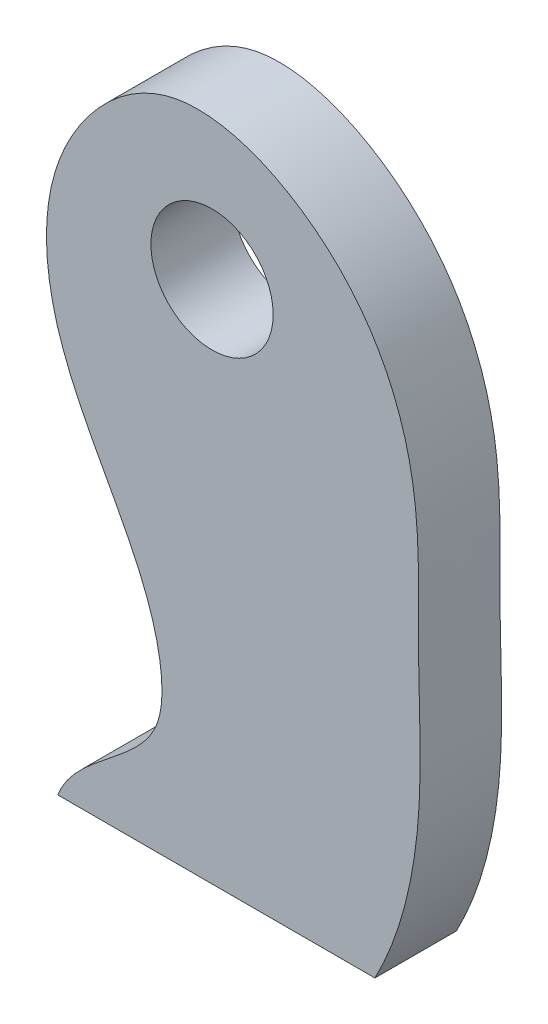
SolidWorks part; units mm, degrees
ref_plane "Front Plane" through (0, 0, 0) normal (0, 0, 1) x (1, 0, 0)
ref_plane "Top Plane" through (0, 0, 0) normal (0, 1, 0) x (1, 0, 0)
ref_plane "Right Plane" through (0, 0, 0) normal (1, 0, 0) x (0, 0, -1)
sketch "Sketch1" plane through (0, 0, 0) normal (0, 0, 1) x (1, 0, 0)
  line L0 (106.6667, 215) -> (533.3333, 215) construction
  line L1 (83.7569, 33.0546) -> (96.1069, 33.0546)
  circle A0 centre (89.762, 53.4491) radius 2.3813
  spline S0 degree 3 poles (83.7569, 33.0546) (84.4287, 34.854) (87.9294, 35.9473) (87.8099, 40.2009) (86.2243, 43.9473) (83.3372, 48.3738) (82.9953, 54.691) (88.0145, 60.4547) (95.3715, 56.9296) (97.9886, 50.8467) (97.7019, 44.9422) (98.0793, 39.05) (97.1378, 35.0067) (96.1069, 33.0546) knots 0 0 0 0 0.094685 0.131841 0.192875 0.295784 0.386703 0.487738 0.604575 0.709963 0.800958 0.891877 1 1 1 1
extrude "Boss-Extrude1" add sketch "Sketch1" along normal blind 3.175
